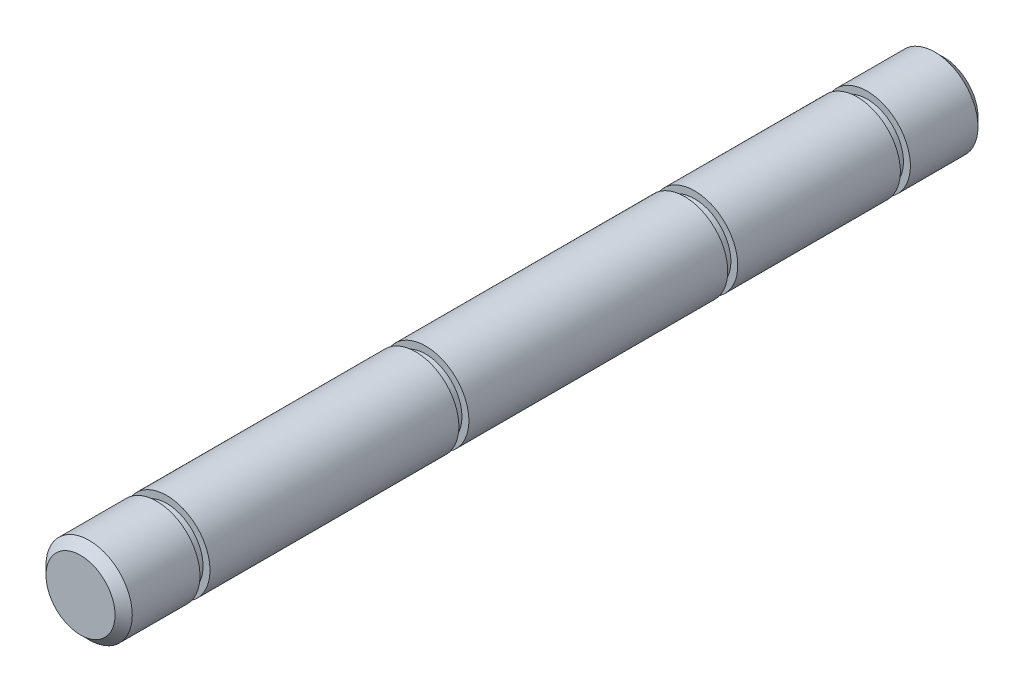
SolidWorks part; units mm, degrees
ref_plane "Front Plane" through (0, 0, 0) normal (0, 0, 1) x (1, 0, 0)
ref_plane "Top Plane" through (0, 0, 0) normal (0, 1, 0) x (1, 0, 0)
ref_plane "Right Plane" through (0, 0, 0) normal (1, 0, 0) x (0, 0, -1)
sketch "Sketch1" plane through (0, 0, 0) normal (0, 0, 1) x (1, 0, 0)
  circle A0 centre (0, 0) radius 3.175
  dimension "D1" = 6.35
extrude "Boss-Extrude1" add sketch "Sketch1" along normal blind 63.5
chamfer "Chamfer1" distance 0.635 angle 45 2 edges at (3.175, 0, 0) (3.175, 0, 63.5)
ref_plane "Plane1" through (0, 0, 19.05) normal (0, 0, -1) x (-1, 0, 0)
sketch "Sketch2" plane through (0, 0, 19.05) normal (0, 0, -1) x (-1, 0, 0)
  circle A0 centre (0, 0) radius 2.667
  circle A1 centre (0, 0) radius 3.175
  dimension "D1" = 5.334
extrude "Cut-Extrude1" cut sketch "Sketch2" along normal blind 0.7366
ref_plane "Plane3" through (0, 0, 6.35) normal (0, 0, -1) x (-1, 0, 0)
sketch "Sketch4" plane through (0, 0, 6.35) normal (0, 0, -1) x (-1, 0, 0)
  circle A0 centre (0, 0) radius 3.175
  circle A1 centre (0, 0) radius 2.667
  dimension "D1" = 5.334
extrude "Cut-Extrude3" cut sketch "Sketch4" along normal blind 0.7366
ref_plane "Plane4" through (0, 0, 31.75) normal (0, 0, -1) x (-1, 0, 0)
mirror "Mirror6" about plane through (0, 0, 31.75) normal (0, 0, -1) of "Cut-Extrude3"
ref_plane "Plane5" through (0, 0, 38.1) normal (0, 0, -1) x (-1, 0, 0)
sketch "Sketch5" plane through (0, 0, 38.1) normal (0, 0, -1) x (-1, 0, 0)
  circle A0 centre (0, 0) radius 3.175
  circle A1 centre (0, 0) radius 2.667
  dimension "D1" = 5.334
extrude "Cut-Extrude4" cut sketch "Sketch5" against normal blind 0.7366
